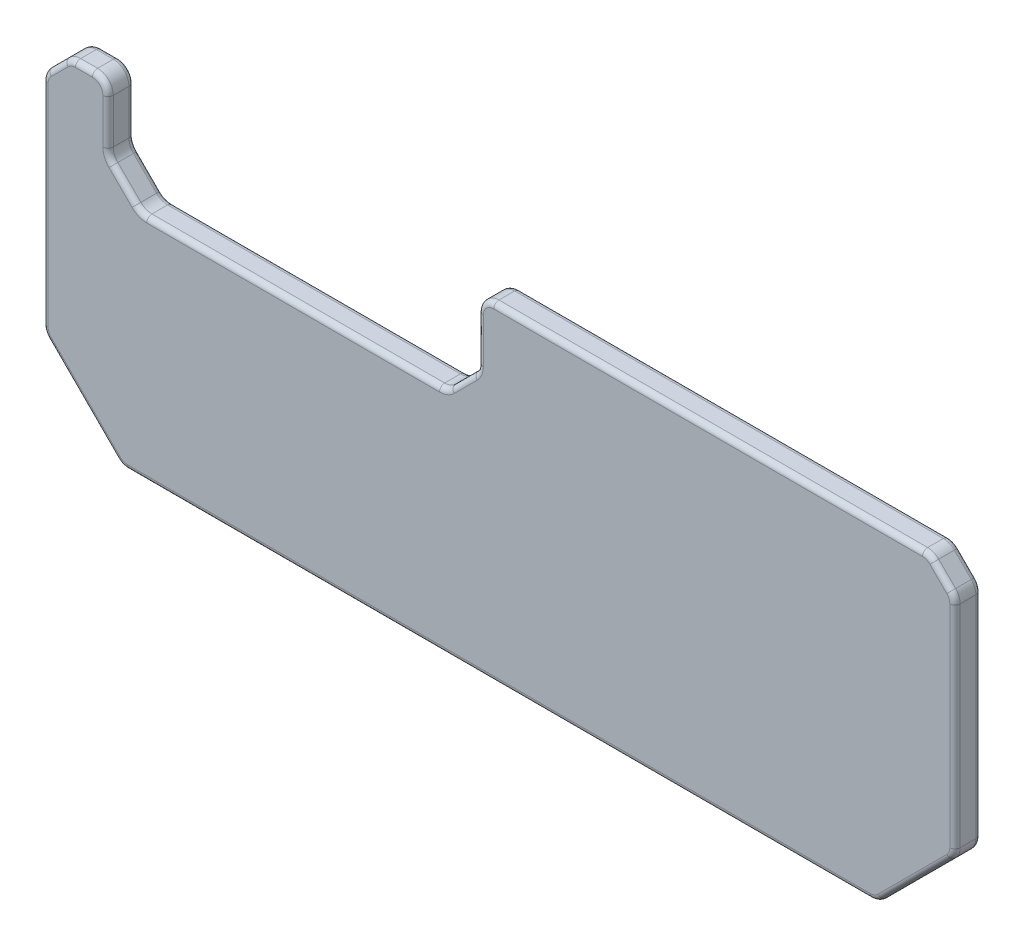
SolidWorks part; units mm, degrees
ref_plane "前视基准面" through (0, 0, 0) normal (0, 0, 1) x (1, 0, 0)
ref_plane "上视基准面" through (0, 0, 0) normal (0, 1, 0) x (1, 0, 0)
ref_plane "右视基准面" through (0, 0, 0) normal (1, 0, 0) x (0, 0, -1)
other "Configuration Table"
sketch "草图1" plane through (0, 0, 0) normal (0, 0, 1) x (1, 0, 0)
  line L1 (-87.5, 56) -> (87.5, 56)
  line L2 (-87.5, 56) -> (-87.5, -7)
  line L3 (-87.5, -7) -> (87.5, -7)
  line L4 (87.5, 56) -> (87.5, -7)
  line L7 (-77, 0) -> (-51.8834, 0) construction
  dimension "D1" = 7
extrude "凸台-拉伸1" add sketch "草图1" along normal blind 5
sketch "草图2" plane through (0, 0, 5) normal (0, 0, 1) x (1, 0, 0)
  line L21 (-75, 56) -> (-4, 56)
  line L31 (-4, 43.1716) -> (-4, 56)
  line L32 (-10.1716, 37) -> (-4, 43.1716)
  line L33 (-68.8284, 37) -> (-10.1716, 37)
  line L34 (-75, 43.1716) -> (-68.8284, 37)
  line L35 (-75, 56) -> (-75, 43.1716)
extrude "切除-拉伸1" cut sketch "草图2" against normal blind 5
chamfer "倒角1" distance 15 angle 45 2 edges at (-87.5, -7, 2.5) (87.5, -7, 2.5)
chamfer "倒角2" distance 5 angle 45 2 edges at (87.5, 56, 2.5) (-87.5, 56, 2.5)
sketch "草图4" plane through (0, -7, 0) normal (0, -1, 0) x (1, 0, 0)
  line L0 (-38.5, 0) -> (-38.5, -3) construction
  line L1 (-72.5, 0) -> (72.5, 0) construction
  line L2 (-23.5, -3) -> (-53.5, -3)
  line L3 (-53.5, -3) -> (-51.7679, 0)
  line L4 (-51.7679, 0) -> (-25.2321, 0)
  line L5 (-23.5, -3) -> (-25.2321, 0)
  line L6 (0, 0) -> (0, 19.5802) construction
  line L7 (38.5, 0) -> (38.5, -3) construction
  line L8 (23.5, -3) -> (25.2321, 0)
  line L9 (51.7679, 0) -> (25.2321, 0)
  line L10 (53.5, -3) -> (51.7679, 0)
  line L11 (23.5, -3) -> (53.5, -3)
  dimension "D1" = 3
  dimension "D2" = 60
  dimension "D3" = 30
  dimension "D4" = 38.5
extrude "凸台-拉伸2" add sketch "草图4" against normal blind 25 from surface at -7
sketch "草图5" plane through (0, 37, 0) normal (0, 1, 0) x (1, 0, 0)
  line L0 (-68.8284, 0) -> (-10.1716, 0) construction
  line L1 (-73.5, 0) -> (-5.5, 0)
  line L2 (-73.5, 0) -> (-73.5, 5)
  line L3 (-73.5, 5) -> (-5.5, 5)
  line L4 (-5.5, 0) -> (-5.5, 5)
  line L6 (-74, 245) -> (-74, 0) construction
  line L7 (-5, 0) -> (-5, 245) construction
  line L8 (82.5, 0) -> (-4, 0) construction
  line L9 (3.5, 0) -> (73.5, 0)
  line L10 (3.5, 0) -> (3.5, 5)
  line L11 (3.5, 5) -> (73.5, 5)
  line L12 (73.5, 0) -> (73.5, 5)
  line L14 (74, 0) -> (74, 217) construction
  line L17 (3, 0) -> (3, 217) construction
  line L18 (55.3, 5) -> (21.7, 5) construction
  line L19 (-5, 5) -> (-74, 5) construction
  dimension "D1" = 0.5
  dimension "D2" = 0.5
  dimension "D3" = 0.5
  dimension "D4" = 0.5
extrude "凸台-拉伸4" add sketch "草图5" against normal blind 2 from surface at -12 contours L2 L1 L4 L3 | L10 L9 L12 L11 starting at face at (38.5, 25, -1.5)
fillet "圆角1" radius 3 13 edges at (-4, 56, 2.5) (-4, 43.1716, 2.5) (-10.1716, 37, 2.5) (-68.8284, 37, 2.5) (-75, 43.1716, 2.5) (-75, 56, 2.5) (72.5, -7, 2.5) (87.5, 8, 2.5) (87.5, 51, 2.5) (82.5, 56, 2.5) (-72.5, -7, 2.5) (-87.5, 8, 2.5) (-82.5, 56, 2.5)
fillet "圆角2" radius 3 1 edges at (-87.5, 51, 2.5)
fillet "圆角3" radius 1 56 edges at (-87.2716, 50.9054, 0) (-85, 53.5, 0) (-82.4054, 55.7716, 0) (-79.6287, 56, 0) (-75.8787, 55.1213, 0) (-75, 48.7071, 0) (-74.7716, 43.2662, 0) (-71.9142, 40.0858, 0) (-68.7338, 37.2284, 0) (-39.5, 37, 0) (-10.2662, 37.2284, 0) (-7.0858, 40.0858, 0) (-4.2284, 43.2662, 0) (-4, 48.7071, 0) (-3.1213, 55.1213, 0) (40.1287, 56, 0) (82.4054, 55.7716, 0) (85, 53.5, 0) (87.2716, 50.9054, 0) (87.5, 29.5, 0) (87.2716, 8.0946, 0) (80, 0.5, 0) (72.4054, -6.7716, 0) (0, -7, 0) (-72.4054, -6.7716, 0) (-80, 0.5, 0) (-87.2716, 8.0946, 0) (-87.2716, 50.9054, 5) (-85, 53.5, 5) (-82.4054, 55.7716, 5) (-79.6287, 56, 5) (-75.8787, 55.1213, 5) (-75, 48.7071, 5) (-74.7716, 43.2662, 5) (-71.9142, 40.0858, 5) (-68.7338, 37.2284, 5) (-39.5, 37, 5) (-10.2662, 37.2284, 5) (-7.0858, 40.0858, 5) (-4.2284, 43.2662, 5) (-4, 48.7071, 5) (-3.1213, 55.1213, 5) (40.1287, 56, 5) (82.4054, 55.7716, 5) (85, 53.5, 5) (87.2716, 50.9054, 5) (87.5, 29.5, 5) (87.2716, 8.0946, 5) (80, 0.5, 5) (72.4054, -6.7716, 5) (0, -7, 5) (-72.4054, -6.7716, 5) (-80, 0.5, 5) (-87.2716, 8.0946, 5) (-87.5, 29.5, 0) (-87.5, 29.5, 5)
